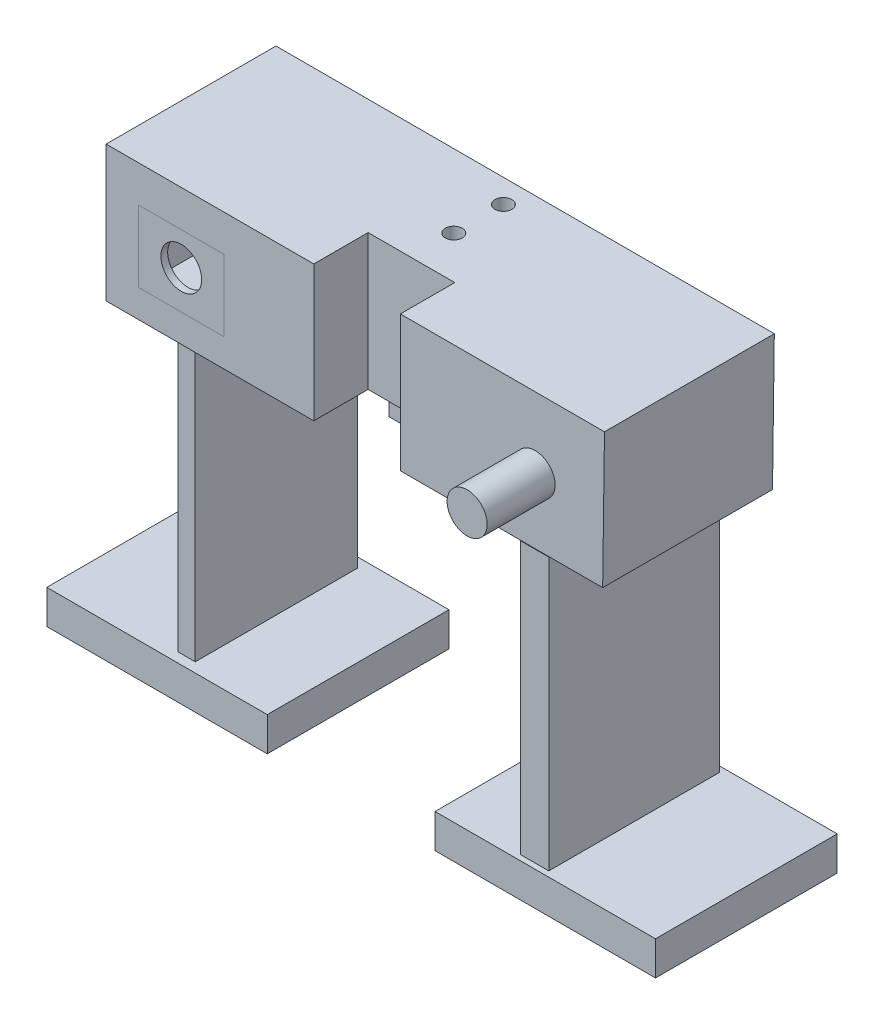
SolidWorks part; units mm, degrees
ref_plane "前基準面" through (0, 0, 0) normal (0, 0, 1) x (1, 0, 0)
ref_plane "上基準面" through (0, 0, 0) normal (0, 1, 0) x (1, 0, 0)
ref_plane "右基準面" through (0, 0, 0) normal (1, 0, 0) x (0, 0, -1)
sketch "草圖1" plane through (0, 0, 0) normal (0, 1, 0) x (1, 0, 0)
  line L1 (-44, 12.5) -> (44, 12.5)
  line L2 (-44, 12.5) -> (-44, -12.5)
  line L3 (-44, -12.5) -> (44, -12.5)
  line L4 (44, 12.5) -> (44, -12.5)
  line L5 (-44, 12.5) -> (44, -12.5) construction
  line L6 (-44, -12.5) -> (44, 12.5) construction
  point P0 (0, 0)
  dimension "D1" = 88
  dimension "D2" = 25
extrude "填料-伸長2" add sketch "草圖1" along normal blind 20
sketch "草圖2" plane through (0, 0, 0) normal (0, -1, 0) x (1, 0, 0)
  line L0 (44, -12.5) -> (-44, -12.5) construction
  line L1 (-6.3745, 12.5) -> (6.3745, 12.5)
  line L2 (-6.3745, 12.5) -> (-6.3745, -12.5)
  line L3 (-6.3745, -12.5) -> (6.3745, -12.5)
  line L4 (6.3745, 12.5) -> (6.3745, -12.5)
  line L5 (-6.3745, 12.5) -> (6.3745, -12.5) construction
  line L6 (-6.3745, -12.5) -> (6.3745, 12.5) construction
  point P0 (0, 0)
sketch "草圖4" plane through (0, 0, 0) normal (0, -1, 0) x (1, 0, 0)
  line L1 (-26.9309, 11.9428) -> (-24.3791, 11.9428)
  line L2 (-26.9309, 11.9428) -> (-26.9309, -11.9428)
  line L3 (-26.9309, -11.9428) -> (-24.3791, -11.9428)
  line L4 (-24.3791, 11.9428) -> (-24.3791, -11.9428)
  line L5 (-26.9309, 11.9428) -> (-24.3791, -11.9428) construction
  line L6 (-26.9309, -11.9428) -> (-24.3791, 11.9428) construction
  point P0 (-25.655, 0)
extrude "填料-伸長5" add sketch "草圖4" along normal blind 40
sketch "草圖5" plane through (0, 0, 0) normal (0, -1, 0) x (1, 0, 0)
  line L1 (24.1057, 12.5769) -> (28.298, 12.5769)
  line L2 (24.1057, 12.5769) -> (24.1057, -12.5769)
  line L3 (24.1057, -12.5769) -> (28.298, -12.5769)
  line L4 (28.298, 12.5769) -> (28.298, -12.5769)
  line L5 (24.1057, 12.5769) -> (28.298, -12.5769) construction
  line L6 (24.1057, -12.5769) -> (28.298, 12.5769) construction
  point P0 (26.2018, 0)
extrude "填料-伸長6" add sketch "草圖5" along normal blind 40
sketch "草圖6" plane through (0, -40, 0) normal (0, -1, 0) x (1, 0, 0)
  line L1 (-44.8001, 13.3732) -> (44.8001, 13.3732)
  line L2 (-44.8001, 13.3732) -> (-44.8001, -13.3732)
  line L3 (-44.8001, -13.3732) -> (44.8001, -13.3732)
  line L4 (44.8001, 13.3732) -> (44.8001, -13.3732)
  line L5 (-44.8001, 13.3732) -> (44.8001, -13.3732) construction
  line L6 (-44.8001, -13.3732) -> (44.8001, 13.3732) construction
  point P0 (0, 0)
extrude "填料-伸長7" add sketch "草圖6" along normal blind 5
sketch "草圖7" plane through (0, 0, -12.5) normal (0, 0, -1) x (-1, 0, 0)
  line L1 (19.5799, 14.6119) -> (32.1799, 14.6119)
  line L2 (19.5799, 14.6119) -> (19.5799, 4.1119)
  line L3 (19.5799, 4.1119) -> (32.1799, 4.1119)
  line L4 (32.1799, 14.6119) -> (32.1799, 4.1119)
  line L5 (19.5799, 14.6119) -> (32.1799, 4.1119) construction
  line L6 (19.5799, 4.1119) -> (32.1799, 14.6119) construction
  point P0 (25.8799, 9.3619)
  dimension "D1" = 10.5
  dimension "D2" = 12.6
extrude "除料-伸長1" cut sketch "草圖7" against normal through all
sketch "草圖8" plane through (0, 0, 12.5) normal (0, 0, 1) x (1, 0, 0)
  line L0 (-32.1799, 14.6119) -> (-32.1799, 4.1119)
  line L1 (-32.1799, 14.6119) -> (-19.5799, 14.6119)
  line L2 (-32.1799, 4.1119) -> (-19.5799, 4.1119)
  line L3 (-19.5799, 14.6119) -> (-19.5799, 4.1119)
extrude "填料-伸長8" add sketch "草圖8" against normal blind 1 separate body
sketch "草圖9" plane through (0, 0, 11.5) normal (0, 0, -1) x (-1, 0, 0)
  circle A0 centre (-25.8799, 9.3619) radius 3
sketch "草圖10" plane through (0, 0, 12.5) normal (0, 0, 1) x (1, 0, 0)
  circle A0 centre (26.2018, 9.5584) radius 2.95
extrude "填料-伸長9" add sketch "草圖10" along normal blind 10
extrude "填料-伸長10" add sketch "草圖2" along normal blind 5
sketch "草圖14" plane through (0, -45, 0) normal (0, -1, 0) x (1, 0, 0)
  line L0 (-44.8001, -13.3732) -> (44.8001, -13.3732) construction
  line L1 (-12.3463, 13.3732) -> (12.3463, 13.3732)
  line L2 (-12.3463, 13.3732) -> (-12.3463, -13.3732)
  line L3 (-12.3463, -13.3732) -> (12.3463, -13.3732)
  line L4 (12.3463, 13.3732) -> (12.3463, -13.3732)
  line L5 (-12.3463, 13.3732) -> (12.3463, -13.3732) construction
  line L6 (-12.3463, -13.3732) -> (12.3463, 13.3732) construction
  point P0 (0, 0)
extrude "除料-伸長3" cut sketch "草圖14" against normal blind 10
sketch "草圖15" plane through (0, -5, 0) normal (0, -1, 0) x (1, 0, 0)
  line L1 (-6.3745, 1.4406) -> (6.3745, 1.4406)
  line L2 (-6.3745, 1.4406) -> (-6.3745, 12.5)
  line L3 (-6.3745, 12.5) -> (6.3745, 12.5)
  line L4 (6.3745, 1.4406) -> (6.3745, 12.5)
  line L5 (-6.3745, 1.4406) -> (6.3745, 12.5) construction
  line L6 (-6.3745, 12.5) -> (6.3745, 1.4406) construction
  point P0 (0, 6.9703)
extrude "除料-伸長4" cut sketch "草圖15" against normal blind 5
sketch "草圖16" plane through (0, 0, 12.5) normal (0, 0, 1) x (1, 0, 0)
  circle A0 centre (-25.8799, 9.751) radius 3
extrude "除料-伸長5" cut sketch "草圖16" against normal blind 5
hole_wizard "M3 螺紋孔3" positions "草圖23" profile "草圖24" tap size "M3" standard "ISO" end condition through all
sketch "草圖23" plane through (0, -5, 0) normal (0, -1, 0) x (-1, 0, 0)
  point P0 (0, 1.7373)
sketch "草圖24" plane through (0, -5, -1.7373) normal (1, 0, 0) x (0, 0, -1)
  line L0 (0, 0) -> (0, 25)
  line L1 (0, 25) -> (1.25, 25)
  line L2 (1.25, 25) -> (1.25, 0.2308)
  line L3 (1.25, 0.2308) -> (1.525, 0)
  line L5 (1.525, 0) -> (0, 0)
  line L6 (-1.25, 0.2308) -> (-1.525, 0) construction
  line L11 (0, -6.35) -> (0, 107.95) construction
  dimension "貫穿螺孔鑽直徑" = 2.5
  dimension "貫穿螺孔鑽深度" = 25
  dimension "近端錐孔直徑" = 3.05
  dimension "近端錐孔角度" = 100
cosmetic thread "鑽孔螺紋4" parameters "D2"=3
sketch "草圖25" plane through (0, -5, 0) normal (0, -1, 0) x (1, 0, 0)
  line L0 (0, -1.7373) -> (0, -9.0373)
hole_wizard "M3 螺紋孔4" positions "草圖26" profile "草圖27" tap size "M3" standard "ISO" end condition through all
sketch "草圖26" plane through (0, -5, 0) normal (0, -1, 0) x (-1, 0, 0)
  point P0 (0, 9.0373)
sketch "草圖27" plane through (0, -5, -9.0373) normal (1, 0, 0) x (0, 0, -1)
  line L0 (0, 0) -> (0, 25)
  line L1 (0, 25) -> (1.25, 25)
  line L2 (1.25, 25) -> (1.25, 0.2308)
  line L3 (1.25, 0.2308) -> (1.525, 0)
  line L5 (1.525, 0) -> (0, 0)
  line L6 (-1.25, 0.2308) -> (-1.525, 0) construction
  line L11 (0, -6.35) -> (0, 107.95) construction
  dimension "貫穿螺孔鑽直徑" = 2.5
  dimension "貫穿螺孔鑽深度" = 25
  dimension "近端錐孔直徑" = 3.05
  dimension "近端錐孔角度" = 100
cosmetic thread "鑽孔螺紋5" parameters "D2"=3
sketch "草圖29" plane through (0, 0, 12.5) normal (0, 0, 1) x (1, 0, 0)
  line L0 (-36.9368, 20) -> (-36.9368, 0)
  line L1 (-44, 20) -> (44, 20) construction
  line L2 (-44, 0) -> (24.1057, 0) construction
  line L3 (-36.9368, 0) -> (-44, 0)
  line L4 (-44, 0) -> (-44, 20)
  line L5 (-44, 20) -> (-36.9368, 20)
extrude "除料-伸長6" cut sketch "草圖29" against normal through all
sketch "草圖30" plane through (0, 0, 12.5) normal (0, 0, 1) x (1, 0, 0)
  line L0 (36.4149, 20) -> (36.149, 0)
  line L1 (-36.9368, 20) -> (44, 20) construction
  line L2 (28.298, 0) -> (44, 0) construction
  line L3 (36.149, 0) -> (44, 0)
  line L4 (44, 0) -> (44, 20)
  line L5 (44, 20) -> (36.4149, 20)
extrude "除料-伸長7" cut sketch "草圖30" against normal through all
sketch "草圖31" plane through (0, 0, 12.5) normal (0, 0, 1) x (1, 0, 0)
  line L0 (-6.3745, 0) -> (-6.3745, 20)
  line L1 (-36.9368, 20) -> (36.4149, 20) construction
  line L2 (6.3745, 0) -> (6.3745, 20)
  line L3 (6.3745, 20) -> (-6.3745, 20)
extrude "除料-伸長8" cut sketch "草圖31" against normal blind 8 and the other way through all
